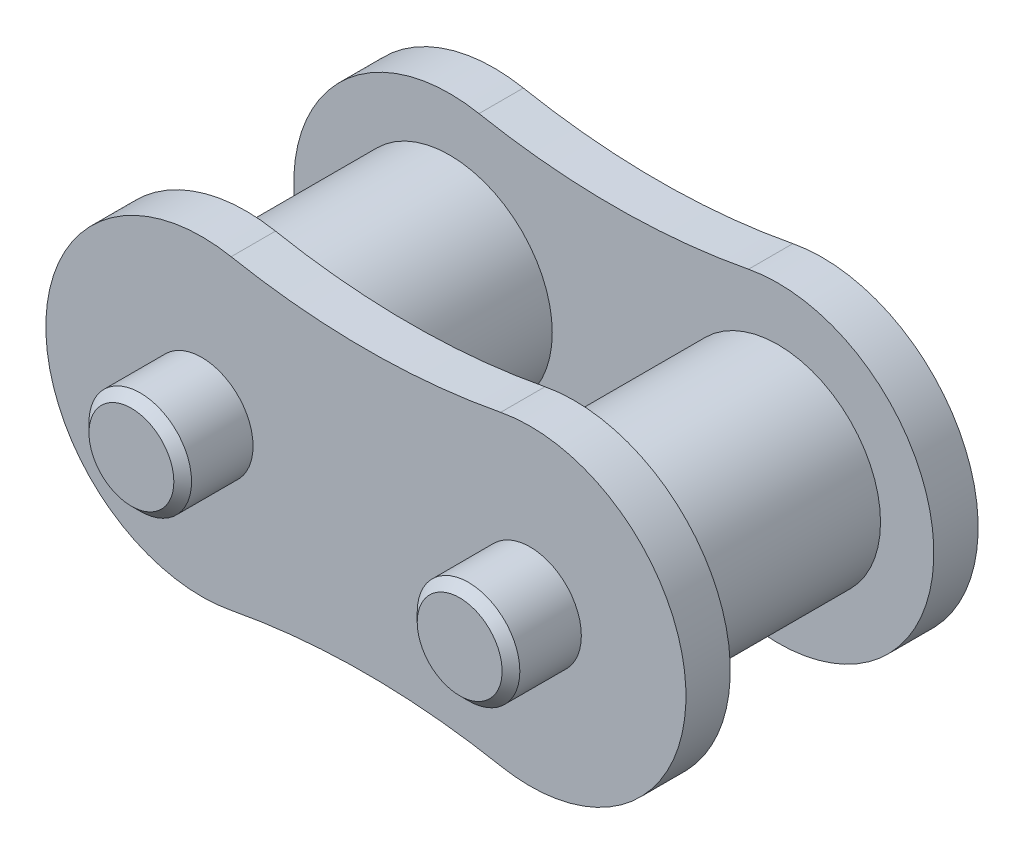
SolidWorks part; units mm, degrees
ref_plane "前视基准面" through (0, 0, 0) normal (0, 0, 1) x (1, 0, 0)
ref_plane "上视基准面" through (0, 0, 0) normal (0, 1, 0) x (1, 0, 0)
ref_plane "右视基准面" through (0, 0, 0) normal (1, 0, 0) x (0, 0, -1)
sketch "草图1" plane through (0, 0, 0) normal (0, 0, 1) x (1, 0, 0)
  line L0 (-12.7, 0) -> (12.7, 0) construction
  line L1 (0, 10.8585) -> (0, -10.8585) construction
  line L2 (12.7, 0) -> (35.31, 0) construction
  line L3 (35.31, 0) -> (51.06, 0) construction
  circle A0 centre (-12.7, 0) radius 12.065
  circle A1 centre (12.7, 0) radius 12.065
  circle A2 centre (0, 66.2389) radius 55.3804
  circle A3 centre (0, -66.2389) radius 55.3804
  circle A4 centre (-12.7, 0) radius 7.94
  circle A5 centre (12.7, 0) radius 7.94
  circle A6 centre (-12.7, 0) radius 3.97
  circle A7 centre (12.7, 0) radius 3.97
  point P16 (46.2, 0)
  point P18 (41.99, 0)
  point P19 (14.7, 0)
  dimension "h2" = 24.13
  dimension "d1" = 15.88
  dimension "d2" = 7.94
  dimension "p" = 25.4
  dimension "h3" = 21.717
  dimension "b2" = 22.61
  dimension "b1" = 15.75
  dimension "b4" = 33.5
  dimension "P1" = 29.29
  dimension "z" = 2
sketch "草图2" plane through (0, 0, 0) normal (0, 0, 1) x (1, 0, 0)
  circle A0 centre (12.7, 0) radius 7.94 construction
  circle A1 centre (-12.7, 0) radius 7.94 construction
  circle A2 centre (12.7, 0) radius 7.94
  circle A3 centre (-12.7, 0) radius 7.94
extrude "拉伸1" add sketch "草图2" along normal mid plane 15.75
sketch "草图3" plane through (0, 0, 7.875) normal (0, 0, 1) x (1, 0, 0)
  circle A0 centre (-12.7, 0) radius 12.065 construction
  arc A1 (-10.4282, 11.8492) -> (-10.4282, -11.8492) centre (-12.7, 0) ccw
  circle A2 centre (12.7, 0) radius 12.065 construction
  arc A3 (10.4282, -11.8492) -> (10.4282, 11.8492) centre (12.7, 0) ccw
  circle A4 centre (0, 66.2389) radius 55.3804 construction
  arc A5 (-10.4282, 11.8492) -> (10.4282, 11.8492) centre (0, 66.2389) ccw
  circle A6 centre (0, -66.2389) radius 55.3804 construction
  arc A7 (10.4282, -11.8492) -> (-10.4282, -11.8492) centre (0, -66.2389) ccw
extrude "拉伸2" add sketch "草图3" along normal blind 3.43
mirror "镜向1" about plane through (0, 0, 0) normal (0, 0, 1) of "拉伸2"
sketch "草图5" plane through (0, 0, 0) normal (0, 0, 1) x (1, 0, 0)
  line L0 (12.7, 0) -> (37.302, -6.3167) construction
  line L1 (-12.7, 0) -> (12.7, 0) construction
  line L2 (-12.7, 0) -> (-776.8532, -96.535)
  line L4 (0, -100.5309) -> (-768.1907, -165.1058) construction
  line L5 (37.302, -6.3167) -> (59.5602, -18.5533) construction
  arc A0 (30.9597, -197.0153) -> (-12.7, 0) centre (0, -100.5309) ccw
  arc A1 (-776.8532, -96.535) -> (-783.5035, -232.504) centre (-768.1907, -165.1058) ccw
  arc A2 (-783.5035, -232.504) -> (30.9597, -197.0153) centre (-441.1553, 1274.3085) ccw
  dimension "R2" = 202.6597
  dimension "R1" = 138.2317
  dimension "a" = 770.9
  dimension "La" = 770.2266
  dimension "L2" = 299.6078
  dimension "L" = 825
  dimension "L1" = 193.0074
curve "组合曲线1"
sketch "草图4" plane through (0, 0, 0) normal (0, 0, 1) x (1, 0, 0)
  circle A0 centre (12.7, 0) radius 3.97 construction
  circle A1 centre (-12.7, 0) radius 3.97 construction
  circle A2 centre (12.7, 0) radius 3.97
  circle A3 centre (-12.7, 0) radius 3.97
extrude "拉伸3" add sketch "草图4" against normal mid plane 33.5
chamfer "倒角1" distance 0.686 angle 45 4 edges at (16.67, 0, -16.75) (-8.73, 0, -16.75) (16.67, 0, 16.75) (-8.73, 0, 16.75)
equation "\"D1@拉伸1\" = \"b1@草图1\""
equation "\"D1@拉伸2\" = (  \"b2@草图1\" - \"D1@拉伸1\" )  / 2"
equation "\"D1@拉伸3\" = \"b4@草图1\""
equation "\"D1@倒角1\" = \"D1@拉伸2\" / 5"
equation "\"h3@草图1\" = \"h2@草图1\" * 0.9"
